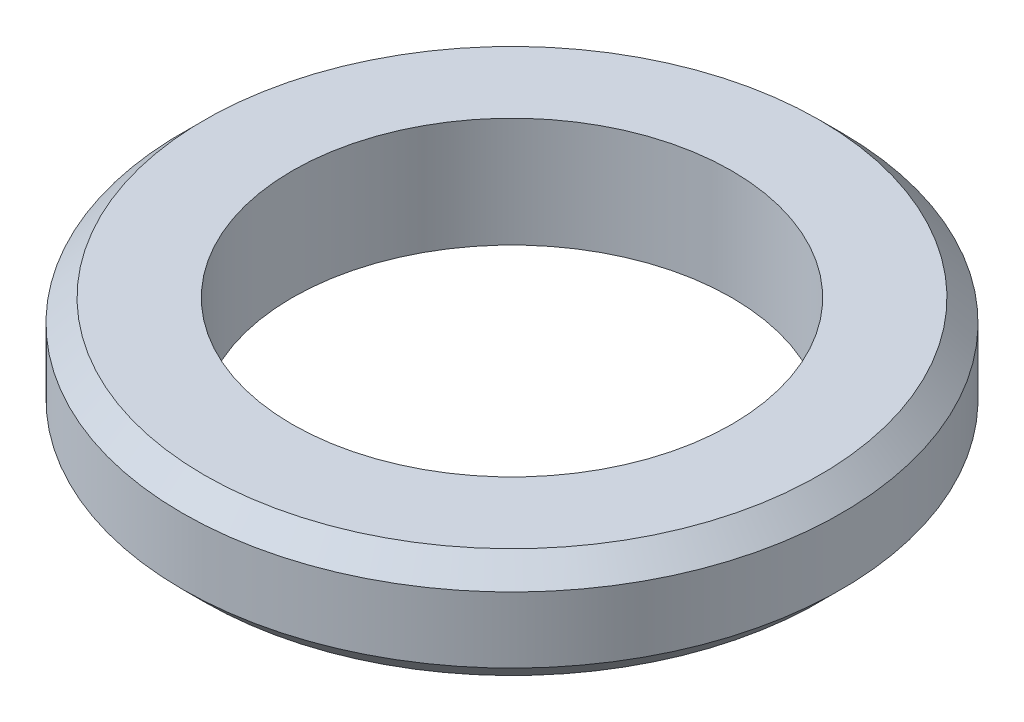
SolidWorks part; units mm, degrees
ref_plane "Front Plane" through (0, 0, 0) normal (0, 0, 1) x (1, 0, 0)
ref_plane "Top Plane" through (0, 0, 0) normal (0, 1, 0) x (1, 0, 0)
ref_plane "Right Plane" through (0, 0, 0) normal (1, 0, 0) x (0, 0, -1)
sketch "Sketch1" plane through (0, 0, 0) normal (0, 1, 0) x (1, 0, 0)
  circle A0 centre (0, 0) radius 5
  circle A1 centre (0, 0) radius 7.5
  dimension "D1" = 10
  dimension "D2" = 15
extrude "Corpo Ø15×2.5" add sketch "Sketch1" along normal blind 2.5
chamfer "Chanfros 0.5×45°" distance 0.5 angle 45 2 edges at (0, 0, 7.5) (0, 2.5, 7.5)
